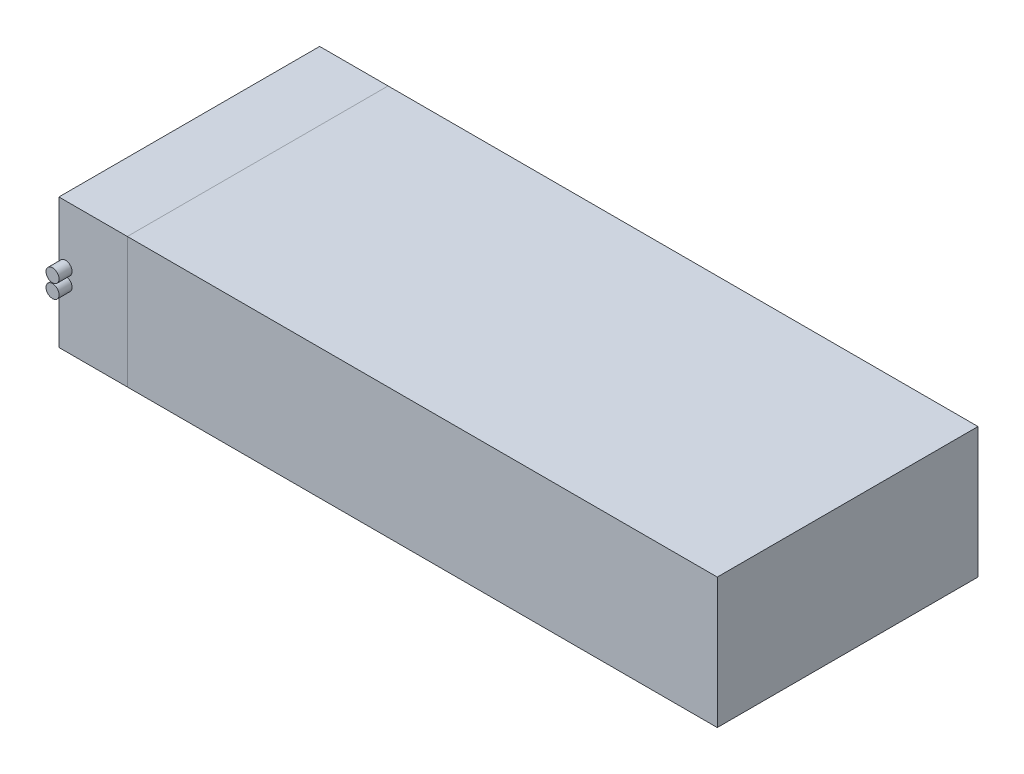
SolidWorks part; units mm, degrees
ref_plane "Front Plane" through (0, 0, 0) normal (0, 0, 1) x (1, 0, 0)
ref_plane "Top Plane" through (0, 0, 0) normal (0, 1, 0) x (1, 0, 0)
ref_plane "Right Plane" through (0, 0, 0) normal (1, 0, 0) x (0, 0, -1)
sketch "Sketch1" plane through (0, 0, 0) normal (0, 1, 0) x (1, 0, 0)
  line L1 (0, 0) -> (50.5, 0)
  line L2 (0, 0) -> (0, 20)
  line L3 (0, 20) -> (50.5, 20)
  line L4 (50.5, 0) -> (50.5, 20)
  dimension "D1" = 50.5
  dimension "D2" = 20
extrude "Boss-Extrude1" add sketch "Sketch1" along normal blind 10
sketch "Sketch3" plane through (0, 0, 0) normal (0, 0, 1) x (1, 0, 0)
  line L0 (0, 10) -> (0, 0) construction
  line L1 (0, 0) -> (50.5, 0) construction
  circle A9 centre (0.51, 4.5) radius 0.5
  circle A11 centre (0.51, 5.55) radius 0.5
  dimension "D1" = 2
  dimension "D3" = 0.51
  dimension "D2" = 1
  dimension "D4" = 4.5
sketch "Sketch4" plane through (0, 0, 0) normal (0, 0, 1) x (1, 0, 0)
  line L0 (5.25, 10) -> (5.25, 0)
  line L1 (0, 10) -> (50.5, 10) construction
  line L2 (0, 0) -> (50.5, 0) construction
  line L3 (0, 10) -> (0, 0) construction
  dimension "D1" = 5.25
split line "Split Line1"
extrude "Boss-Extrude7" add sketch "Sketch3" along normal blind 1 contours A11 | A9
